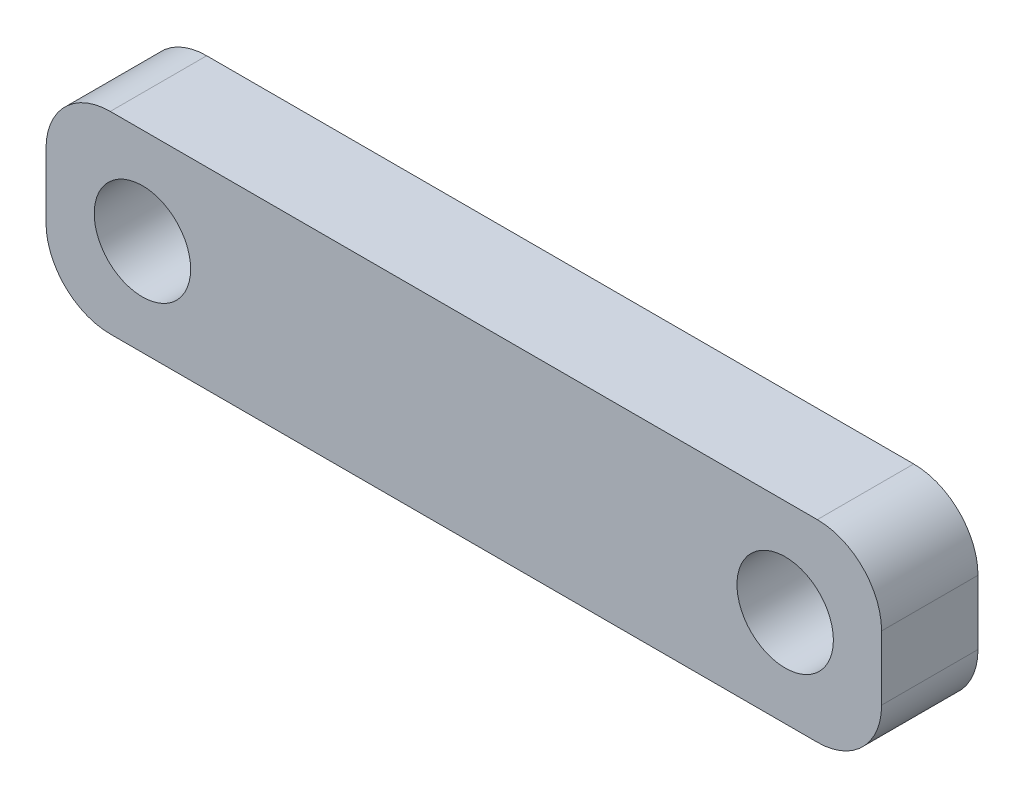
SolidWorks part; units mm, degrees
ref_plane "Front Plane" through (0, 0, 0) normal (0, 0, 1) x (1, 0, 0)
ref_plane "Top Plane" through (0, 0, 0) normal (0, 1, 0) x (1, 0, 0)
ref_plane "Right Plane" through (0, 0, 0) normal (1, 0, 0) x (0, 0, -1)
sketch "Sketch1" plane through (0, 0, 0) normal (0, 0, 1) x (1, 0, 0)
  line L1 (0, 0) -> (26, 0)
  line L2 (0, 0) -> (0, 6)
  line L3 (0, 6) -> (26, 6)
  line L4 (26, 0) -> (26, 6)
  circle A0 centre (3, 3) radius 1.5
  circle A1 centre (23, 3) radius 1.5
  dimension "D1" = 3
  dimension "D2" = 20
  dimension "D4" = 3
  dimension "D6" = 3
  dimension "D7" = 3
  dimension "D3" = 3
  dimension "D5" = 3
extrude "Boss-Extrude1" add sketch "Sketch1" along normal blind 3
fillet "Fillet1" radius 2 4 edges at (0, 0, 1.5) (26, 0, 1.5) (26, 6, 1.5) (0, 6, 1.5)
